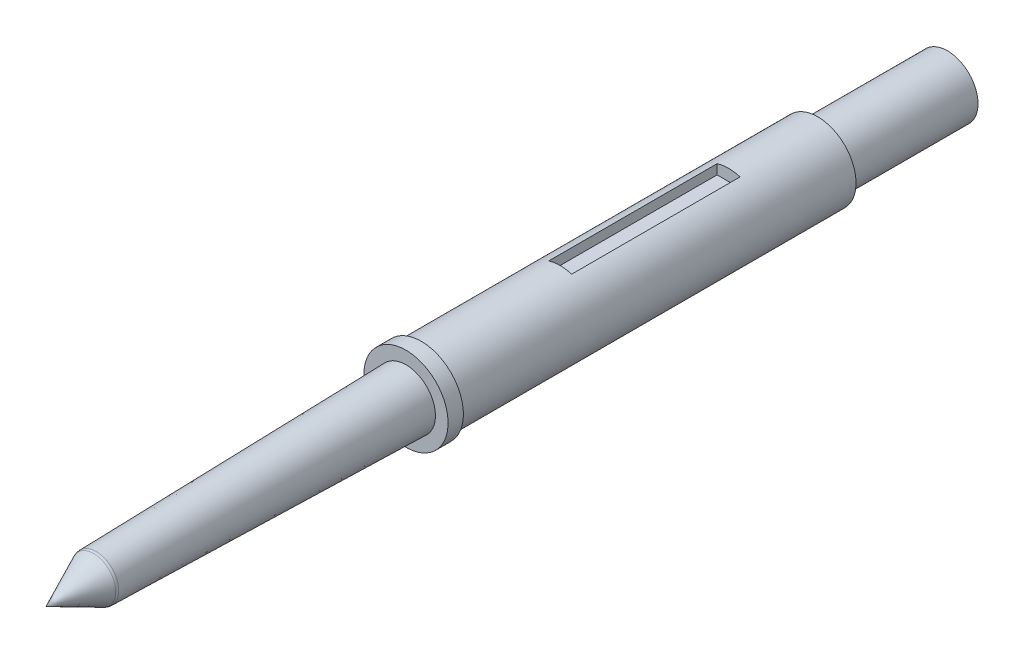
SolidWorks part; units mm, degrees
ref_plane "Front Plane" through (0, 0, 0) normal (0, 0, 1) x (1, 0, 0)
ref_plane "Top Plane" through (0, 0, 0) normal (0, 1, 0) x (1, 0, 0)
ref_plane "Right Plane" through (0, 0, 0) normal (1, 0, 0) x (0, 0, -1)
sketch "Sketch3" plane through (0, 0, 0) normal (1, 0, 0) x (0, 0, -1)
  line L0 (0, 0) -> (-259.5858, 0) construction
  line L4 (-177.8, 0) -> (0, 0)
  line L6 (-176.5581, 4.6891) -> (-112.3, 6.1099)
  line L7 (-112.3, 6.1099) -> (-112.3, 8.7312)
  line L8 (-112.3, 8.7312) -> (-109.125, 8.7312)
  line L11 (-26.8925, 7.9375) -> (-26.8925, 6.35)
  line L12 (-26.8925, 6.35) -> (0, 6.35)
  line L13 (0, 6.35) -> (0, 0)
  line L15 (-115.8, 6.0325) -> (-115.8, 0) construction
  line L16 (-112.3, 6.1099) -> (-168.6233, 6.1099) construction
  line L22 (-177.8, 3.4195) -> (-177.8, 0) construction
  line L23 (-177.0628, 4.5723) -> (-186.9554, 0)
  line L24 (-186.9554, 0) -> (-177.8, 0)
  line L26 (-26.8925, 16.9069) -> (-26.8925, -16.9069) construction
  line L30 (-109.125, 8.7312) -> (-109.125, 7.9375)
  line L32 (-109.125, 7.9375) -> (-26.8925, 7.9375)
  arc A0 (-177.8, 3.4195) -> (-176.5581, 4.6891) centre (-176.53, 3.4195) cw
  point P3 (-115.8, 6.0325)
  point P5 (-177.8, 4.6617)
  dimension "D2" = 65.5
  dimension "D9" = 1.27
  dimension "D3" = 17.4625
  dimension "D4" = 12.7
  dimension "D5" = 15.875
  dimension "D6" = 177.8
  dimension "D7" = 3.175
  dimension "D10" = 3.5
  dimension "D11" = 12.065
  dimension "D13" = 1.267
revolve "Revolve2" add sketch "Sketch3" angle 360 about L0
ref_plane "Plane1" through (0, 7.9375, 0) normal (0, 1, 0) x (1, 0, 0)
sketch "Sketch4" plane through (0, 7.9375, 0) normal (0, 1, 0) x (1, 0, 0)
  line L0 (0, 0) -> (0, -62.8551) construction
  line L1 (2.3813, -80.3176) -> (-2.3812, -80.3176)
  line L2 (2.3813, -80.3176) -> (2.3813, -45.3926)
  line L3 (2.3813, -45.3926) -> (-2.3812, -45.3926)
  line L4 (-2.3812, -80.3176) -> (-2.3812, -45.3926)
  line L5 (2.3813, -80.3176) -> (-2.3812, -45.3926) construction
  line L6 (2.3813, -45.3926) -> (-2.3812, -80.3176) construction
  point P0 (0, -62.8551)
  dimension "D1" = 34.925
  dimension "D2" = 4.7625
extrude "Cut-Extrude1" cut sketch "Sketch4" against normal blind 2.3813
